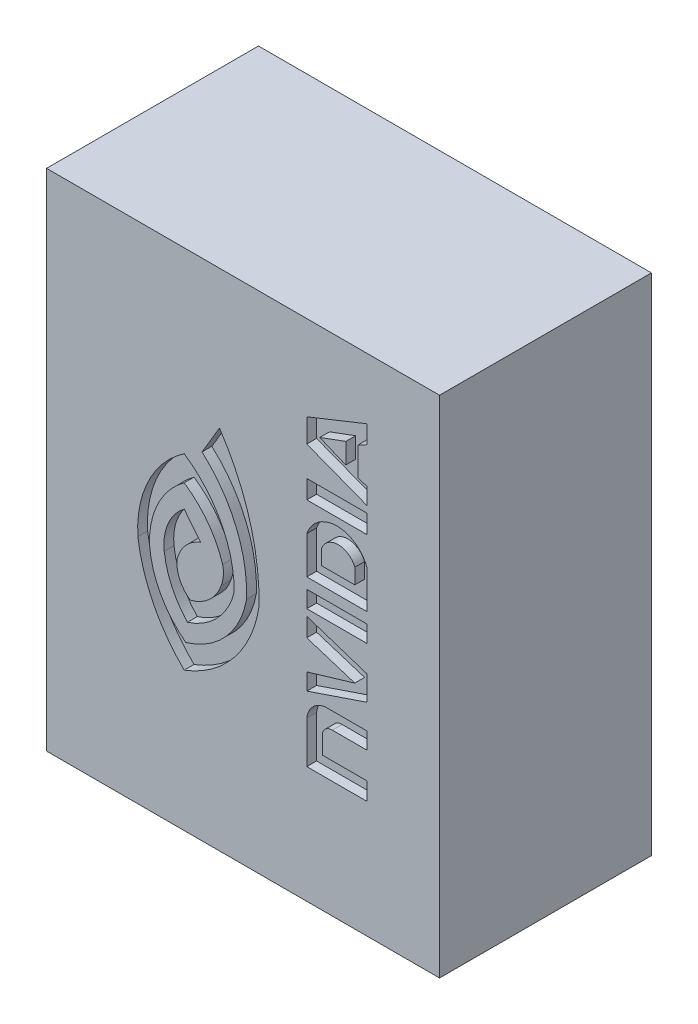
SolidWorks part; units mm, degrees
ref_plane "Front Plane" through (0, 0, 0) normal (0, 0, 1) x (1, 0, 0)
ref_plane "Top Plane" through (0, 0, 0) normal (0, 1, 0) x (1, 0, 0)
ref_plane "Right Plane" through (0, 0, 0) normal (1, 0, 0) x (0, 0, -1)
sketch "Sketch1" plane through (0, 0, 0) normal (0, 1, 0) x (1, 0, 0)
  line L1 (51, -27.5) -> (-51, -27.5)
  line L2 (51, -27.5) -> (51, 27.5)
  line L3 (51, 27.5) -> (-51, 27.5)
  line L4 (-51, -27.5) -> (-51, 27.5)
  line L5 (51, -27.5) -> (-51, 27.5) construction
  line L6 (51, 27.5) -> (-51, -27.5) construction
  point P0 (0, 0)
  dimension "D1" = 102
  dimension "D2" = 55
extrude "Boss-Extrude1" add sketch "Sketch1" along normal blind 131
sketch "Sketch2" plane through (0, 0, 27.5) normal (0, 0, 1) x (1, 0, 0)
  line L0 (-118.4019, 120.6819) -> (-118.4019, 587.3486) construction
  line L1 (32.2227, 30.2891) -> (16.5434, 30.2891)
  line L2 (16.5434, 30.2891) -> (16.5434, 41.2133)
  line L3 (21.264, 46.1122) -> (32.2227, 46.1122)
  line L4 (32.2227, 46.1122) -> (32.2227, 41.7968)
  line L6 (20.5711, 39.4119) -> (20.5711, 34.8922)
  line L7 (20.5711, 34.8922) -> (32.2227, 34.8922)
  line L8 (32.2227, 34.8922) -> (32.2227, 30.2891)
  line L9 (32.2227, 58.9145) -> (32.2227, 52.5853)
  line L10 (32.2227, 52.5853) -> (16.5434, 47.263)
  line L11 (16.5434, 47.263) -> (16.5434, 51.5784)
  line L12 (16.5434, 51.5784) -> (29.0013, 55.2942)
  line L13 (29.0013, 55.2942) -> (16.5434, 59.2447)
  line L14 (16.5434, 59.2447) -> (16.5434, 64.0887)
  line L15 (16.5434, 64.0887) -> (32.2227, 58.9145)
  line L16 (32.2227, 65.7817) -> (32.2227, 70.1555)
  line L17 (32.2227, 70.1555) -> (16.5434, 70.1555)
  line L18 (16.5434, 70.1555) -> (16.5434, 65.7817)
  line L19 (16.5434, 65.7817) -> (32.2227, 65.7817)
  line L20 (32.2227, 72.9302) -> (16.5434, 72.9302)
  line L21 (16.5434, 72.9302) -> (16.5434, 82.6652)
  line L22 (32.2227, 72.9302) -> (32.2227, 82.6652)
  line L23 (20.3359, 81.187) -> (20.3359, 77.3676)
  line L24 (20.3359, 77.3676) -> (29.0013, 77.3676)
  line L25 (29.0013, 77.3676) -> (29.0013, 81.3185)
  line L26 (16.5434, 95.0677) -> (16.5434, 90.2476)
  line L27 (16.5434, 90.2476) -> (32.2227, 90.2476)
  line L28 (32.2227, 90.2476) -> (32.2227, 95.0677)
  line L29 (32.2227, 95.0677) -> (16.5434, 95.0677)
  line L30 (32.2227, 96.7577) -> (32.2227, 101.0731)
  line L31 (32.2227, 101.0731) -> (29.8432, 101.8633)
  line L32 (29.8432, 101.8633) -> (29.8432, 109.239)
  line L33 (29.8432, 109.239) -> (32.2227, 110.4841)
  line L34 (32.2227, 110.4841) -> (32.2227, 115.184)
  line L35 (32.2227, 115.184) -> (16.5434, 108.9278)
  line L36 (16.5434, 108.9278) -> (16.5434, 102.796)
  line L37 (16.5434, 102.796) -> (32.2227, 96.7577)
  line L38 (26.6618, 108.4577) -> (19.9062, 105.9556)
  line L39 (19.9062, 105.9556) -> (26.6618, 103.1533)
  line L40 (26.6618, 103.1533) -> (26.6618, 108.4577)
  line L41 (-6.1157, 95.0677) -> (-10.6406, 87.4279)
  line L42 (-15.269, 72.2621) -> (-11.0316, 66.9255)
  line L43 (23.1734, 41.7968) -> (32.2227, 41.7968)
  arc A0 (16.5434, 82.6652) -> (32.2227, 82.6652) centre (24.383, 80.0165) cw
  arc A1 (20.3359, 81.187) -> (29.0013, 81.3185) centre (24.6931, 79.6395) cw
  arc A2 (21.264, 46.1122) -> (16.5434, 41.2133) centre (22.0933, 40.5893) ccw
  arc A3 (23.1734, 41.7968) -> (20.5711, 39.4119) centre (23.0647, 39.3032) ccw
  arc A4 (-6.1157, 95.0677) -> (4.1397, 60.0572) centre (-56.5598, 61.2841) cw
  arc A5 (4.1397, 60.0572) -> (-15.2694, 36.0713) centre (-25.929, 64.5427) cw
  arc A6 (-15.2694, 36.0713) -> (-27.3047, 60.0572) centre (13.5469, 65.5428) cw
  arc A7 (-27.3047, 60.0572) -> (-15.2694, 84.7212) centre (0.4795, 61.7677) cw
  arc A8 (-15.2694, 84.7212) -> (-2.2958, 60.0572) centre (-31.8805, 60.2394) cw
  arc A9 (-2.2958, 60.0572) -> (-14.4218, 47.263) centre (-19.7631, 64.4688) cw
  arc A10 (-14.4218, 47.263) -> (-20.4573, 60.2091) centre (1.908, 62.7558) cw
  arc A11 (-20.4573, 60.2091) -> (-15.269, 72.2621) centre (-7.3343, 61.7034) cw
  arc A12 (-11.0316, 66.9255) -> (-17.197, 59.7942) centre (-7.5161, 57.6553) ccw
  arc A13 (-17.197, 59.7942) -> (-13.7378, 52.5853) centre (-8.8565, 59.362) ccw
  arc A14 (-13.7378, 52.5853) -> (-5.6967, 59.7942) centre (-16.3529, 63.5915) ccw
  arc A15 (-15.269, 78.1764) -> (-5.2908, 64.8222) centre (-29.4704, 57.1603) cw
  arc A16 (-5.2908, 64.8222) -> (-5.6967, 59.7942) centre (-13.7365, 62.9735) cw
  arc A17 (-15.269, 78.1764) -> (-24.2764, 59.7942) centre (-2.5216, 60.5322) ccw
  arc A18 (-24.2764, 59.7942) -> (-14.8641, 42.498) centre (-0.3412, 61.6103) ccw
  arc A19 (0.9036, 60.0572) -> (-14.8641, 42.498) centre (-21.0467, 63.9089) cw
  arc A20 (-10.6406, 87.4279) -> (0.9036, 60.0572) centre (-33.9913, 61.4594) cw
extrude "Cut-Extrude1" cut sketch "Sketch2" against normal blind 2.54
